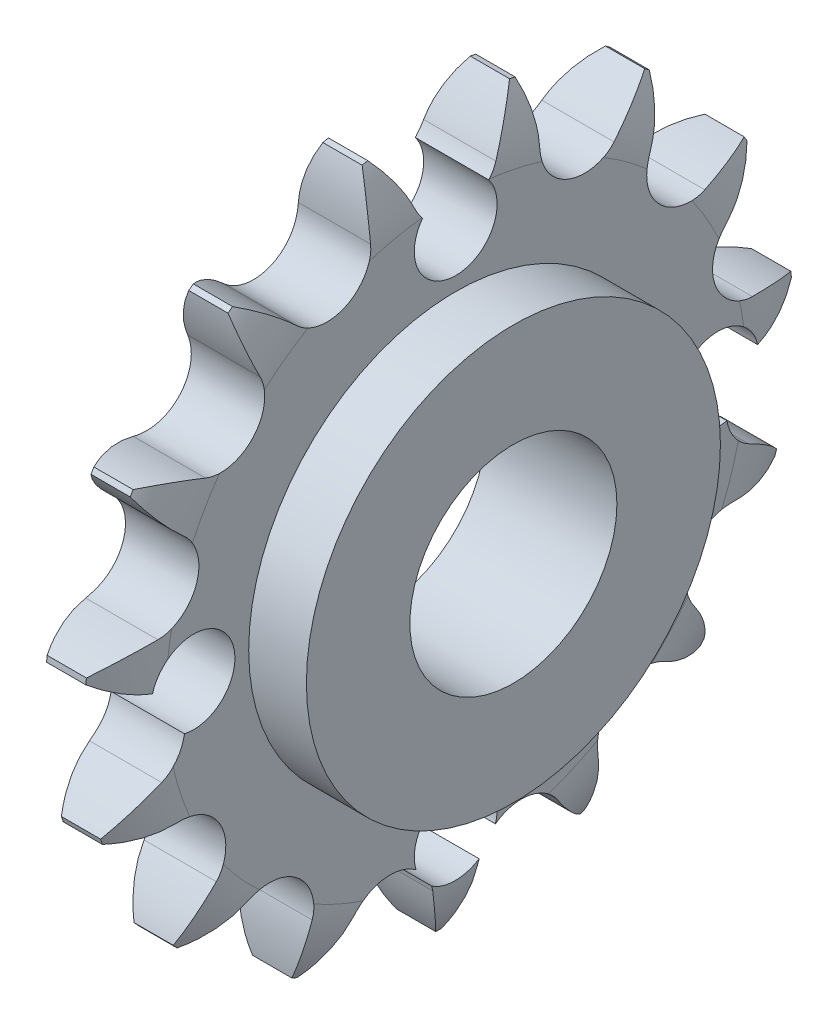
SolidWorks part; units mm, degrees
ref_plane "Plane1" through (0, 0, 0) normal (0, 0, 1) x (1, 0, 0)
ref_plane "Plane2" through (0, 0, 0) normal (0, 1, 0) x (1, 0, 0)
ref_plane "Plane3" through (0, 0, 0) normal (1, 0, 0) x (0, 0, -1)
sketch "Clipboard" plane through (0, 0, 0) normal (0, 1, 0) x (1, 0, 0)
  line L0 (0, 0) -> (9.2004, -2.4653)
  line L1 (-15, 0) -> (100, 0) construction
  line L2 (0, 0) -> (-0.8203, 0.9272)
  line L3 (0, 0) -> (-8.8973, 3.4006)
  line L4 (0, 0) -> (2.9944, 0.8023)
  line L5 (0, 0) -> (-46.8476, -17.4728)
  line L6 (0, 0) -> (-4.4098, -2.9753)
  line L7 (-0.8203, 0.9272) -> (47.2432, 14.7092)
  line L8 (-76.2, 38.1) -> (-74.4, 38.1)
  line L9 (-73.3242, 40.7328) -> (-72.926, 40.7699)
  line L10 (-73.4529, 9.1872) -> (-63.2129, 9.1872)
  circle A0 centre (0, 0) radius 3.175
  circle A1 centre (0, 0) radius 17.7306
  circle A2 centre (0, 0) radius 37.5
  dimension "Dr" = 6.35
  dimension "MHD" = 35.4612
  dimension "Hub_dia" = 75
  dimension "Num_teeth" = 15
  dimension "Pitch" = 9.525
  dimension "Width" = 3.1
  dimension "Side_relief" = 1.238
  dimension "Side_radius" = 9.525
  dimension "Overall_len" = 50
  dimension "Show_teeth" = 15
  dimension "Thickness" = 5.3196
  dimension "OAL" = 50.0005
  dimension "T_dim" = 1.8
  dimension "Fillet_rad" = 0.4
  dimension "Face_width" = 5.32
  dimension "Num_strands" = 1
  dimension "Transv_pitch" = 10.24
  dimension "Plate_wid" = 8.26
sketch "BasProSke" plane through (0, 0, 0) normal (0, 1, 0) x (1, 0, 0)
  line L0 (-10, 0) -> (60, 0) construction
  line L1 (0, 0) -> (0, 20.9886)
  line L2 (0, 0) -> (5.3196, 0)
  line L3 (5.3196, 0) -> (5.3196, 20.9886)
  line L4 (4.0816, 25.6845) -> (1.238, 25.6845)
  arc A0 (0, 20.9886) -> (1.238, 25.6845) centre (9.525, 20.9886) cw
  arc A1 (5.3196, 20.9886) -> (4.0816, 25.6845) centre (-4.2054, 20.9886) ccw
  dimension "Thickness" = 5.3196
  dimension "D1" = 9.525
  dimension "G1" = 1.238
  dimension "G2" = 1.238
  dimension "Diameter" = 51.369
revolve "Base-Revolve" add sketch "BasProSke" angle 360 about L0
sketch "TooCutSke" plane through (0, 0, 0) normal (1, 0, 0) x (0, 0, -1)
  line L0 (0, 22.9381) -> (2.9518, 21.6851) construction
  line L1 (0, 0) -> (0, 107) construction
  line L2 (0, 22.9381) -> (-10, 22.9381) construction
  line L3 (0, 22.9381) -> (-2.9518, 21.6851) construction
  arc A0 (2.9518, 21.6851) -> (5.5304, 25.5938) centre (14.876, 16.6236) cw
  arc A1 (2.9518, 21.6851) -> (-2.9518, 21.6851) centre (0, 22.9381) cw
  arc A2 (-2.9518, 21.6851) -> (-5.5304, 25.5938) centre (-14.876, 16.6236) ccw
  arc A3 (5.5304, 25.5938) -> (-5.5304, 25.5938) centre (0, 0) ccw
  dimension "R1" = 3.2067
  dimension "R2" = 12.954
  dimension "Overcut" = 26.1845
  dimension "Seat_radius" = 22.9381
  dimension "X" = 134
extrude "ToothCut" cut sketch "TooCutSke" along normal through all
pattern_circular "TeethCuts" count 15 every 24 about axis through (-10, 0, 0) along (1, 0, 0) of "ToothCut"
sketch "HubNeaOneSke" plane through (0, 0, 0) normal (-1, 0, 0) x (0, 0, 1)
  circle A0 centre (0, 0) radius 17.7306
  dimension "Diameter" = 35.4612
extrude "HubNearOne" [suppressed] add sketch "HubNeaOneSke" along normal blind 44.6809
fillet "HubNearOneFillet" [suppressed] radius 0.4
sketch "HubNeaBotSke" plane through (0, 0, 0) normal (-1, 0, 0) x (0, 0, 1)
  circle A0 centre (0, 0) radius 17.7306
  dimension "Diameter" = 35.4612
extrude "HubNearBoth" [suppressed] add sketch "HubNeaBotSke" along normal blind 22.3405
fillet "HubNearBothFillet" [suppressed] radius 0.4
ref_plane "FarPln" through (5.3196, 0, 0) normal (1, 0, 0) x (0, 0, -1)
sketch "HubFarSke" plane through (5.3196, 0, 0) normal (1, 0, 0) x (0, 0, -1)
  circle A0 centre (0, 0) radius 17.7306
  dimension "Diameter" = 35.4612
extrude "HubFar" [suppressed] add sketch "HubFarSke" along normal blind 22.3405
fillet "HubFarFillet" [suppressed] radius 0.4
sketch "BorSke" plane through (0, 0, 0) normal (1, 0, 0) x (0, 0, -1)
  circle A0 centre (0, 0) radius 5
  dimension "Diameter" = 10
extrude "Bore" cut sketch "BorSke" along normal mid plane 100.001
sketch "KeySke" plane through (0, 0, 0) normal (1, 0, 0) x (0, 0, -1)
  line L0 (-2, 0) -> (-2, 6.8)
  line L1 (-2, 6.8) -> (2, 6.8)
  line L2 (2, 6.8) -> (2, 0)
  line L3 (0, 0) -> (0, 34) construction
  line L4 (-2, 0) -> (2, 0)
  dimension "Offset" = 6.8
  dimension "Width" = 4
extrude "Keyway" [suppressed] cut sketch "KeySke" along normal mid plane 100.001
pattern_circular "Keyway2" [suppressed] count 2 every 90 about axis through (-10, 0, 0) along (1, 0, 0)
sketch "Sketch1" plane through (5.3196, 0, 0) normal (1, 0, 0) x (0, 0, -1)
  circle A0 centre (0, 0) radius 15
  circle A1 centre (0, 0) radius 7.5
  dimension "D1" = 15
  dimension "D2" = 30
extrude "Boss-Extrude1" add sketch "Sketch1" along normal offset from surface (24.6804 mm away) 30 up to face at (0, 0, -5)
sketch "Sketch3" plane through (5.3196, 0, 0) normal (1, 0, 0) x (0, 0, -1)
  circle A1 centre (0, 0) radius 7.5
  circle A2 centre (0, 0) radius 7.5
  dimension "D1" = 0
extrude "Cut-Extrude2" cut sketch "Sketch3" against normal blind 18.5
sketch "Sketch2" plane through (30, 0, 0) normal (1, 0, 0) x (0, 0, -1)
  circle A0 centre (0, 0) radius 17.7976
extrude "Cut-Extrude1" cut sketch "Sketch2" against normal blind 20.5
sketch "Sketch4" plane through (9.5, 0, 0) normal (1, 0, 0) x (0, 0, -1)
  line L0 (0, 19) -> (0, 0) construction
  circle A0 centre (0, 19) radius 3
  circle A1 centre (19, 0) radius 3
  circle A2 centre (0, -19) radius 3
  circle A3 centre (-19, 0) radius 3
  point P13 (0, 0)
  dimension "D2" = 6
  dimension "D1" = 19
  dimension "D3" = 4
extrude "Cut-Extrude4" cut sketch "Sketch4" against normal blind 18.5
equation "' \"Pitch@Clipboard\" = 12.7"
equation "' \"Num_strands@Clipboard\" = 1"
equation "' \"Num_teeth@Clipboard\" = 9"
equation "' \"Hub_dia@Clipboard\" = 50"
equation "' \"Overall_len@Clipboard\" = 3"
equation "' \"Diameter@BorSke\" = 12"
equation "' \"T_dim@Clipboard\" = 1"
equation "' \"Width@KeySke\" = 2"
equation "' \"Dr@Clipboard\" = 8.51"
equation "' \"Face_width@Clipboard\" = 7.2"
equation "' \"Side_radius@Clipboard\" = 12.7"
equation "' \"Side_relief@Clipboard\" = 1.27"
equation "' \"Transv_pitch@Clipboard\" = 13.92"
equation "' \"Show_teeth@Clipboard\" = 9"
equation "' \"Fillet_rad@Clipboard\" = 0.6"
equation "' \"Plate_wid@Clipboard\" = 11.8"
equation "\"Num_teeth@Clipboard\" = int( \"Num_teeth@Clipboard\" )"
equation "\"Num_teeth@Clipboard\" = ((sgn( \"Num_teeth@Clipboard\" - 5.0)+1)*( \"Num_teeth@Clipboard\" - 5.0))/2 +5.0"
equation "\"Num_teeth@Clipboard\" = ((sgn( \"Num_teeth@Clipboard\" - 200.0)-1)*( \"Num_teeth@Clipboard\" - 200.0))/-2 +200.0"
equation "\"MHD@Clipboard\" = \"Pitch@Clipboard\" * (1.0 / tan(3.14159265 / \"Num_teeth@Clipboard\" )) - 1.04 * \"Plate_wid@Clipboard\" - 0.76"
equation "\"Thickness@Clipboard\"  = \"Face_width@Clipboard\" + (\"Num_strands@Clipboard\" - 1) * \"Transv_pitch@Clipboard\""
equation "\"OAL@Clipboard\" = \"Thickness@Clipboard\" + 2 * \"Fillet_rad@Clipboard\" + 1"
equation "\"MHD@Clipboard\" = ((sgn( \"MHD@Clipboard\" - \"Hub_dia@Clipboard\" )-1)*( \"MHD@Clipboard\" - \"Hub_dia@Clipboard\" ))/-2+ \"Hub_dia@Clipboard\""
equation "\"OAL@Clipboard\" = ((sgn( \"OAL@Clipboard\" - \"Overall_len@Clipboard\" )+1)*( \"OAL@Clipboard\" - \"Overall_len@Clipboard\" ))/2 + \"Overall_len@Clipboard\" + 0.0005"
equation "\"Num_teeth@TeethCuts\" = int( \"Show_teeth@Clipboard\" ) + 1"
equation "\"Num_teeth@TeethCuts\" = ((sgn( \"Num_teeth@TeethCuts\" - \"Num_teeth@Clipboard\" )-1)*( \"Num_teeth@TeethCuts\" - \"Num_teeth@Clipboard\" ))/-2+ \"Num_teeth@Clipboard\""
equation "\"Num_teeth@TeethCuts\" = ((sgn( \"Num_teeth@TeethCuts\" - 2.0)+1)*( \"Num_teeth@TeethCuts\" - 2.0))/2 +2.0"
equation "\"Angle@TeethCuts\" = 360.0 / \"Num_teeth@Clipboard\""
equation "\"Seat_radius@TooCutSke\" = ( \"Pitch@Clipboard\" / 2.0) / sin(3.14159265 / \"Num_teeth@Clipboard\" ) - \"Dr@Clipboard\" / 2.0 + \"Dr@Clipboard\" * 0.505"
equation "\"R1@TooCutSke\"  = \"Dr@Clipboard\" * 0.505"
equation "\"X@TooCutSke\" = 140.0 - (90.0 / \"Num_teeth@Clipboard\")"
equation "\"R2@TooCutSke\" = 0.12 * \"Dr@Clipboard\" * ( \"Num_teeth@Clipboard\" + 2.0)"
equation "\"Overcut@TooCutSke\" = 0.5 + 0.625 * \"Pitch@Clipboard\" - 0.5 * \"Dr@Clipboard\"  +  \"Pitch@Clipboard\" / 2.0 / sin(3.14159265 / \"Num_teeth@Clipboard\" )"
equation "\"Diameter@BasProSke\" = 2.0 * ( 0.625 * \"Pitch@Clipboard\" - 0.5 * \"Dr@Clipboard\"  +  \"Pitch@Clipboard\" / 2.0 / sin(3.14159265 / \"Num_teeth@Clipboard\" ))"
equation "\"Thickness@BasProSke\"  = \"Thickness@Clipboard\""
equation "\"G1@BasProSke\" =  \"Side_relief@Clipboard\""
equation "\"G2@BasProSke\" =  \"Side_relief@Clipboard\""
equation "\"D1@BasProSke\" =  \"Side_radius@Clipboard\""
equation "\"Diameter@HubNeaOneSke\" = \"MHD@Clipboard\""
equation "\"Length@HubNearOne\" = \"OAL@Clipboard\" - \"Thickness@BasProSke\""
equation "\"Diameter@HubNeaBotSke\" = \"MHD@Clipboard\""
equation "\"Length@HubNearBoth\" = ( \"OAL@Clipboard\" - \"Thickness@BasProSke\" ) / 2.0"
equation "\"D1@HubNearOneFillet\" = \"Fillet_rad@Clipboard\""
equation "\"D1@HubNearBothFillet\" = \"Fillet_rad@Clipboard\""
equation "\"Thickness@FarPln\" = \"Thickness@BasProSke\""
equation "\"Diameter@HubFarSke\" = \"MHD@Clipboard\""
equation "\"Length@HubFar\" = ( \"OAL@Clipboard\" - \"Thickness@BasProSke\" ) / 2.0"
equation "\"D1@HubFarFillet\" = \"Fillet_rad@Clipboard\""
equation "\"D1@Bore\" = \"OAL@Clipboard\" * 2.0"
equation "\"D1@Keyway\" = \"OAL@Clipboard\" * 2.0"
equation "\"Offset@KeySke\" = \"T_dim@Clipboard\" + \"Diameter@BorSke\" / 2.0"
